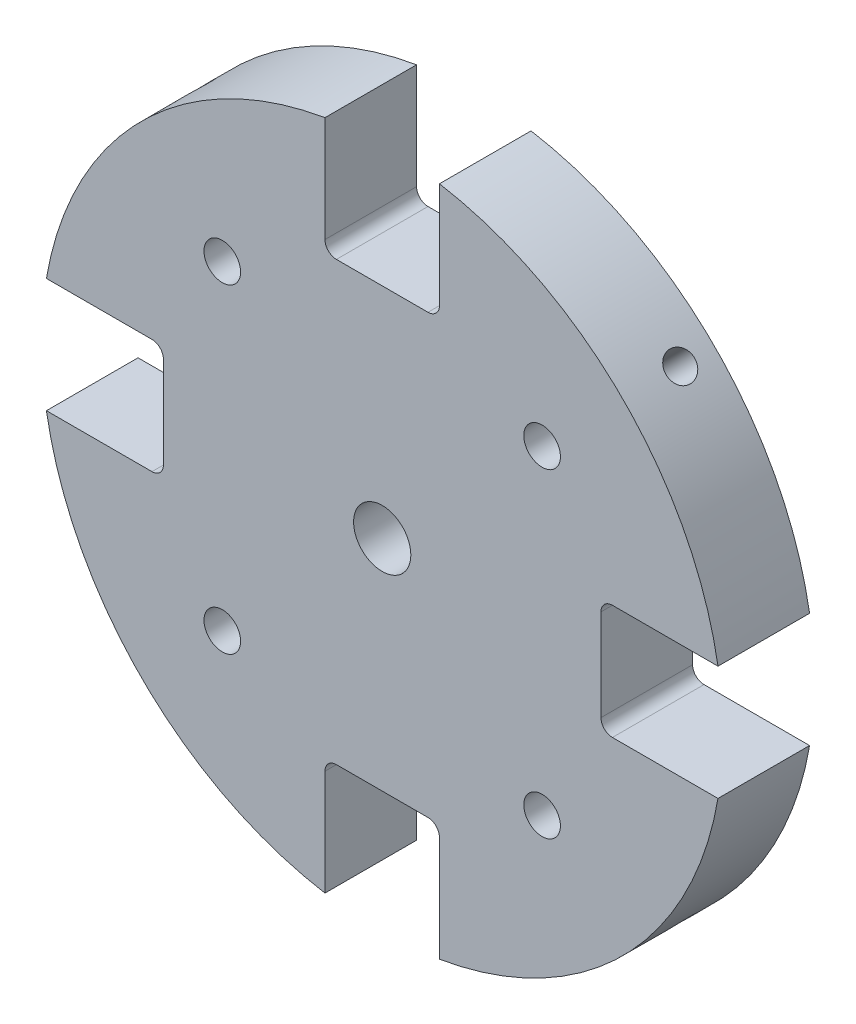
SolidWorks part; units mm, degrees
ref_plane "Front Plane" through (0, 0, 0) normal (0, 0, 1) x (1, 0, 0)
ref_plane "Top Plane" through (0, 0, 0) normal (0, 1, 0) x (1, 0, 0)
ref_plane "Right Plane" through (0, 0, 0) normal (1, 0, 0) x (0, 0, -1)
sketch "Sketch1" plane through (0, 0, 0) normal (0, 0, 1) x (1, 0, 0)
  line L0 (-29.3268, 5) -> (-20.1066, 5)
  line L1 (-29.3268, -5) -> (-20.1066, -5)
  line L2 (29.3268, 5) -> (20.1066, 5)
  line L3 (29.3268, -5) -> (20.1066, -5)
  line L4 (0, 0) -> (19.75, 0) construction
  line L5 (19.1066, 4) -> (19.1066, -4)
  line L6 (-19.1066, 4) -> (-19.1066, -4)
  line L7 (13.9654, 13.9654) -> (0, 0) construction
  line L8 (5, 29.3268) -> (5, 20.1066)
  line L9 (4, 19.1066) -> (-4, 19.1066)
  line L10 (-5, 29.3268) -> (-5, 20.1066)
  line L11 (5, -29.3268) -> (5, -20.1066)
  line L12 (4, -19.1066) -> (-4, -19.1066)
  line L13 (-5, -29.3268) -> (-5, -20.1066)
  line L14 (0, 0) -> (19.1066, 4) construction
  line L15 (0, 0) -> (4, -19.1066) construction
  arc A0 (29.3268, 5) -> (5, 29.3268) centre (0, 0) ccw
  circle A1 centre (0, 0) radius 19.75 construction
  arc A2 (-29.3268, -5) -> (-5, -29.3268) centre (0, 0) ccw
  arc A3 (20.1066, 5) -> (19.1066, 4) centre (20.1066, 4) ccw
  arc A4 (20.1066, -5) -> (19.1066, -4) centre (20.1066, -4) cw
  arc A5 (-20.1066, -5) -> (-19.1066, -4) centre (-20.1066, -4) ccw
  arc A6 (-20.1066, 5) -> (-19.1066, 4) centre (-20.1066, 4) cw
  circle A7 centre (13.9654, 13.9654) radius 1.6
  circle A8 centre (13.9654, -13.9654) radius 1.6
  circle A9 centre (-13.9654, -13.9654) radius 1.6
  circle A10 centre (-13.9654, 13.9654) radius 1.6
  arc A12 (5, 20.1066) -> (4, 19.1066) centre (4, 20.1066) cw
  arc A13 (-5, 20.1066) -> (-4, 19.1066) centre (-4, 20.1066) ccw
  arc A14 (5, -20.1066) -> (4, -19.1066) centre (4, -20.1066) ccw
  arc A15 (-5, -20.1066) -> (-4, -19.1066) centre (-4, -20.1066) cw
  arc A16 (-5, 29.3268) -> (-29.3268, 5) centre (0, 0) ccw
  arc A17 (5, -29.3268) -> (29.3268, -5) centre (0, 0) ccw
  point P14 (19.1066, 5)
  point P17 (19.1066, -5)
  point P20 (-19.1066, -5)
  point P23 (-19.1066, 5)
  point P35 (0, 0)
  dimension "D1" = 59.5
  dimension "D2" = 39.5
  dimension "D4" = 1
  dimension "D3" = 10
  dimension "D6" = 45
  dimension "D10" = 90
  dimension "D7" = 4
  dimension "D9" = 2
extrude "Boss-Extrude1" add sketch "Sketch1" along normal blind 8
hole_wizard "M6x1.0 Tapped Hole1" positions "Sketch4" profile "Sketch5" tap size "M6x1.0" standard "ANSI Metric" end condition up to next
sketch "Sketch4" plane through (0, 0, 8) normal (0, 0, 1) x (1, 0, 0)
  point P0 (0, 0)
sketch "Sketch5" plane through (0, 0, 8) normal (1, 0, 0) x (0, -1, 0)
  line L0 (0, 0) -> (0, 8)
  line L1 (0, 8) -> (2.5, 8)
  line L2 (2.5, 8) -> (2.5, 0)
  line L5 (2.5, 0) -> (0, 0)
  line L11 (0, -6.35) -> (0, 107.95) construction
  dimension "Thru Tap Drill Dia." = 5
  dimension "Thru Tap Drill Depth" = 8
cosmetic thread "Hole Thread1" parameters "D2"=6
ref_plane "Plane2" through (0, 0, 3) normal (0, 0, 1) x (1, 0, 0)
sketch "Sketch8" plane through (0, 0, 3) normal (0, 0, 1) x (1, 0, 0)
  arc A0 (-29.3268, -5) -> (-5, -29.3268) centre (0, 0) ccw construction
  point P0 (-21.0364, -21.0364)
hole_wizard "M3x0.5 Tapped Hole2" positions "3DSketch2" profile "Sketch10" tap size "M3x0.5" standard "ANSI Metric"
sketch3d "3DSketch2"
  point P8 (-21.0364, -21.0364, 3)
sketch "Sketch10" plane through (-21.0364, -21.0364, 3) normal (0, 0, 1) x (0.7071, -0.7071, 0)
  line L0 (0, 0) -> (0, 7)
  line L1 (0, 7) -> (1.25, 6.2489)
  line L2 (1.25, 6.2489) -> (1.25, 0)
  line L5 (1.25, 0) -> (0, 0)
  line L10 (0, 7) -> (-1.25, 6.2489) construction
  line L11 (0, -6.35) -> (0, 107.95) construction
  dimension "Tap Drill Dia." = 2.5
  dimension "Tap Drill Depth" = 7
  dimension "Drill Angle" = 118
cosmetic thread "Hole Thread3" parameters "D1"=6, "D2"=3
pattern_circular "CirPattern4" count 4 over 360 about axis through (0, 0, 8) along (0, 0, -1) of "M3x0.5 Tapped Hole2"
cosmetic thread "Hole Thread4" parameters "D1"=6, "D2"=3
cosmetic thread "Hole Thread5" parameters "D1"=6, "D2"=3
cosmetic thread "Hole Thread6" parameters "D1"=6, "D2"=3
equation "\"D\"= \"D\""
equation "\"DL\"= 59.5"
equation "\"D1@Sketch1\"  = \"DL\""
equation "\"D2@Sketch1\"  = \"DL\"-20"
